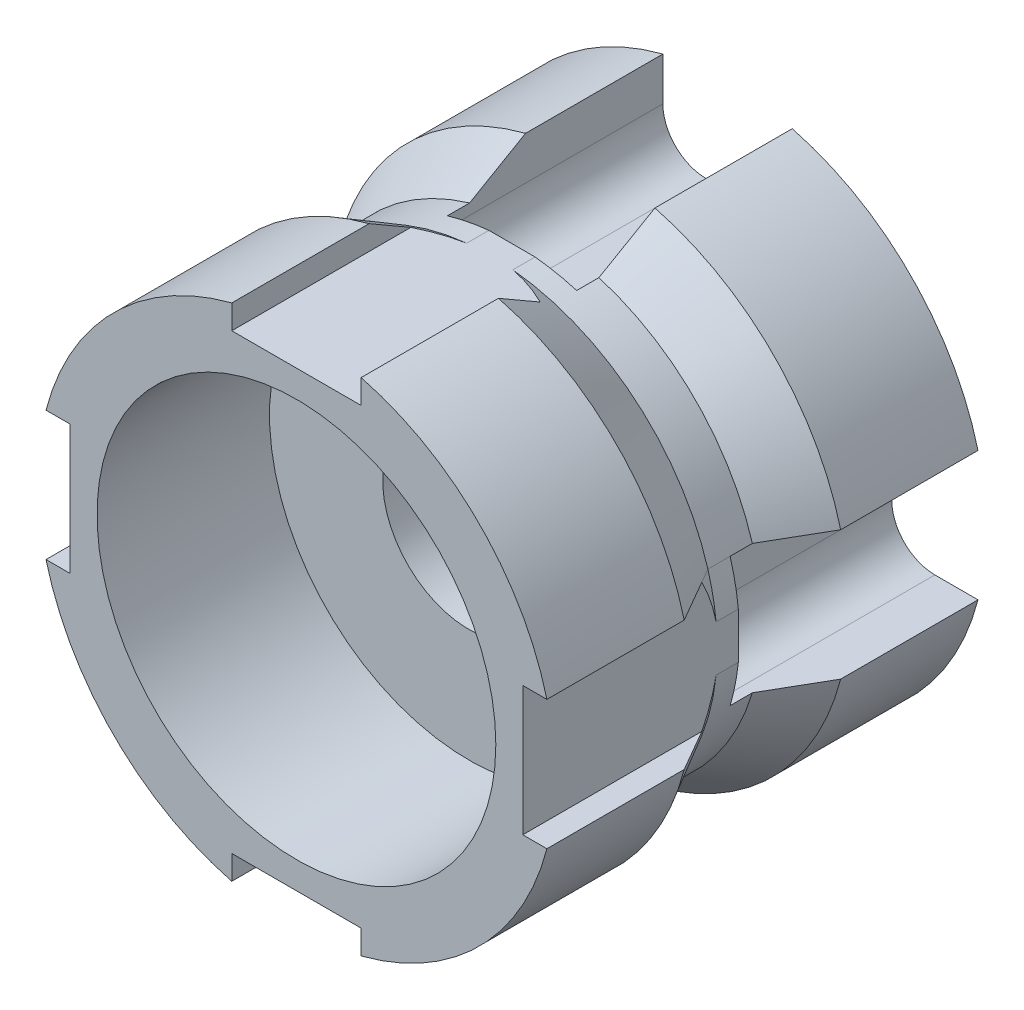
SolidWorks part; units mm, degrees
ref_plane "Front Plane" through (0, 0, 0) normal (0, 0, 1) x (1, 0, 0)
ref_plane "Top Plane" through (0, 0, 0) normal (0, 1, 0) x (1, 0, 0)
ref_plane "Right Plane" through (0, 0, 0) normal (1, 0, 0) x (0, 0, -1)
sketch "Sketch1" plane through (0, 0, 0) normal (0, 0, 1) x (1, 0, 0)
  line L0 (0, 12) -> (0, 7.2431) construction
  line L1 (-3, 10.5) -> (3, 10.5)
  line L2 (3, 10.5) -> (3, 11.619)
  line L3 (-3, 10.5) -> (-3, 11.619)
  line L4 (10.5, 3) -> (11.619, 3)
  line L5 (10.5, 3) -> (10.5, -3)
  line L6 (10.5, -3) -> (11.619, -3)
  line L7 (3, -10.5) -> (3, -11.619)
  line L8 (3, -10.5) -> (-3, -10.5)
  line L9 (-3, -10.5) -> (-3, -11.619)
  line L10 (-10.5, -3) -> (-11.619, -3)
  line L11 (-10.5, -3) -> (-10.5, 3)
  line L12 (-10.5, 3) -> (-11.619, 3)
  arc A0 (-3, 11.619) -> (-11.619, 3) centre (0, 0) ccw
  circle A1 centre (0, 0) radius 5.05
  arc A3 (-11.619, -3) -> (-3, -11.619) centre (0, 0) ccw
  arc A4 (3, -11.619) -> (11.619, -3) centre (0, 0) ccw
  arc A5 (11.619, 3) -> (3, 11.619) centre (0, 0) ccw
  point P12 (0, 10.5)
  point P27 (0, 0)
  dimension "D1" = 24
  dimension "D2" = 10.1
  dimension "D3" = 10.5
  dimension "D5" = 3
  dimension "D6" = 4
extrude "Boss-Extrude1" add sketch "Sketch1" along normal blind 20
sketch "Sketch2" plane through (0, 0, 20) normal (0, 0, 1) x (1, 0, 0)
  circle A0 centre (0, 0) radius 9.25
  dimension "D1" = 18.5
extrude "Cut-Extrude1" cut sketch "Sketch2" against normal blind 8
sketch "Sketch3" plane through (0, 3, 0) normal (0, -1, 0) x (1, 0, 0)
  line L0 (11.619, 10) -> (11.0756, 10) construction
  line L1 (11.619, 20) -> (11.619, 0) construction
  line L2 (2.8981, 10) -> (11.619, 10) construction
  line L3 (10.119, 8.9683) -> (10.119, 11.0317)
  line L4 (10.119, 11.0317) -> (11.619, 13.6297)
  line L5 (11.619, 13.6297) -> (11.619, 6.3703)
  line L6 (10.119, 8.9683) -> (11.619, 6.3703)
  point P9 (10.119, 10)
  dimension "D1" = 1.5
  dimension "D2" = 30
sweep "Cut-Sweep1" cut profiles "Sketch3" path edge at (9.25, 0, 20)
sketch "Sketch4" plane through (0, 0, 12) normal (0, 0, 1) x (1, 0, 0)
  circle A0 centre (0, 0) radius 7
  circle A1 centre (0, 0) radius 4
  dimension "D1" = 14
  dimension "D2" = 8
extrude "Boss-Extrude2" add sketch "Sketch4" against normal blind 2
sketch "Sketch5" plane through (0, 0, 0) normal (0, 0, -1) x (-1, 0, 0)
  line L0 (-11.619, 3) -> (-9.619, 3)
  line L1 (-3, -11.619) -> (3, -11.619)
  line L2 (-3, -11.619) -> (-3, -9.619)
  line L3 (-1, -7.619) -> (1, -7.619)
  line L4 (3, -11.619) -> (3, -9.619)
  line L5 (-11.619, 3) -> (-11.619, -3)
  line L6 (-11.619, -3) -> (-9.619, -3)
  line L7 (-7.619, 1) -> (-7.619, -1)
  line L8 (3, 11.619) -> (3, 9.619)
  line L9 (3, 11.619) -> (-3, 11.619)
  line L10 (-3, 11.619) -> (-3, 9.619)
  line L11 (1, 7.619) -> (-1, 7.619)
  line L12 (11.619, -3) -> (9.619, -3)
  line L13 (11.619, -3) -> (11.619, 3)
  line L14 (11.619, 3) -> (9.619, 3)
  line L15 (7.619, -1) -> (7.619, 1)
  arc A0 (1, -7.619) -> (3, -9.619) centre (1, -9.619) cw
  arc A1 (-3, -9.619) -> (-1, -7.619) centre (-1, -9.619) cw
  arc A2 (9.619, -3) -> (7.619, -1) centre (9.619, -1) cw
  arc A3 (9.619, 3) -> (7.619, 1) centre (9.619, 1) ccw
  arc A4 (3, 9.619) -> (1, 7.619) centre (1, 9.619) cw
  arc A5 (-3, 9.619) -> (-1, 7.619) centre (-1, 9.619) ccw
  arc A6 (-9.619, 3) -> (-7.619, 1) centre (-9.619, 1) cw
  arc A7 (-9.619, -3) -> (-7.619, -1) centre (-9.619, -1) ccw
  point P20 (0, 0)
  point P22 (-3, -7.619)
  dimension "D3" = 2
  dimension "D4" = 2
  dimension "D1" = 4
  dimension "D2" = 4
extrude "Cut-Extrude2" cut sketch "Sketch5" against normal blind 10
